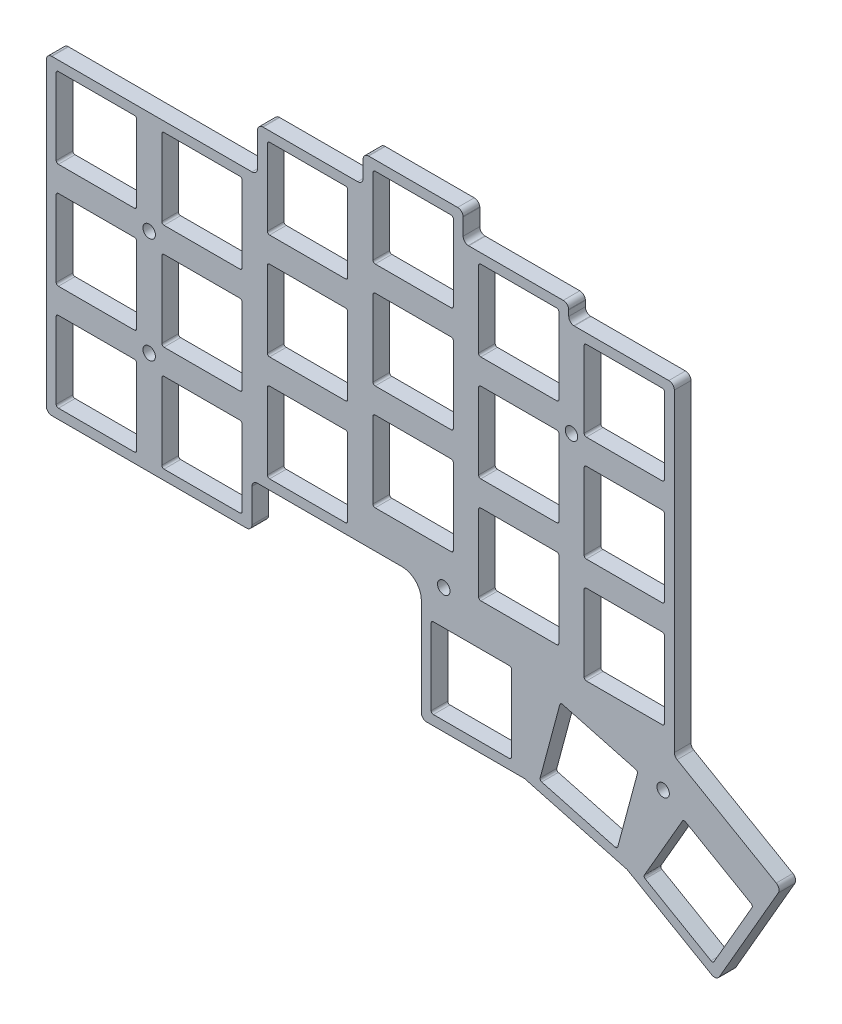
SolidWorks part; units mm, degrees
material "Polyurethane Foam Flexible"
ref_plane "Front Plane" through (0, 0, 0) normal (0, 0, 1) x (1, 0, 0)
ref_plane "Top Plane" through (0, 0, 0) normal (0, 1, 0) x (1, 0, 0)
ref_plane "Right Plane" through (0, 0, 0) normal (1, 0, 0) x (0, 0, -1)
sketch "Sketch1" plane through (0, 0, 0) normal (0, 0, 1) x (1, 0, 0)
  line L84 (-43.4123, 85.1441) -> (-59.4623, 85.1441)
  line L85 (-59.4623, 85.1441) -> (-59.5605, 85.1417)
  line L86 (-60.4623, 84.1441) -> (-60.4623, 81.1441)
  line L87 (-60.4623, 81.1441) -> (-60.4647, 81.0459)
  line L88 (-61.4623, 80.1441) -> (-67.6123, 80.1441)
  line L89 (-67.6123, 80.1441) -> (-72.3623, 80.1441)
  line L90 (-72.3623, 80.1441) -> (-78.5123, 80.1441)
  line L91 (-78.5123, 80.1441) -> (-78.6105, 80.1417)
  line L92 (-79.5123, 79.1441) -> (-79.5123, 73.1441)
  line L93 (-79.5123, 73.1441) -> (-79.5147, 73.0459)
  line L94 (-80.5123, 72.1441) -> (-116.6123, 72.1441)
  line L95 (-116.6123, 72.1441) -> (-116.7105, 72.1417)
  line L96 (-117.6123, 71.1441) -> (-117.6123, 16.9941)
  line L97 (-117.6123, 16.9941) -> (-117.6099, 16.8959)
  line L98 (-116.6123, 15.9941) -> (-101.4373, 15.9941)
  line L99 (-101.4373, 15.9941) -> (-96.6873, 15.9941)
  line L100 (-96.6873, 15.9941) -> (-81.5123, 15.9941)
  line L101 (-81.5123, 15.9941) -> (-81.414, 15.9965)
  line L102 (-80.5123, 16.9941) -> (-80.5123, 22.9941)
  line L103 (-80.5123, 22.9941) -> (-80.5099, 23.0924)
  line L104 (-79.5123, 23.9941) -> (-53.4623, 23.9941)
  line L105 (-53.4623, 23.9941) -> (-53.279, 23.9917)
  line L106 (-49.9623, 20.4941) -> (-49.9623, 2.9441)
  line L107 (-49.9623, 2.9441) -> (-49.9599, 2.8459)
  line L108 (-48.9623, 1.9441) -> (-31.3465, 1.9441)
  line L109 (-31.3465, 1.9441) -> (-12.8184, -3.0205)
  line L110 (-12.8184, -3.0205) -> (2.4374, -11.8284)
  line L111 (2.4374, -11.8284) -> (2.5236, -11.8754)
  line L112 (3.8033, -11.4624) -> (17.3338, 11.973)
  line L113 (17.3338, 11.973) -> (17.3758, 12.0495)
  line L114 (17.4677, 12.4729) -> (17.4677, 76.1441)
  line L115 (17.4677, 76.1441) -> (17.4653, 76.2424)
  line L116 (16.4677, 77.1441) -> (-22.3623, 77.1441)
  line L117 (-22.3623, 77.1441) -> (-22.4605, 77.1465)
  line L118 (-23.3623, 78.1441) -> (-23.3623, 79.1441)
  line L119 (-23.3623, 79.1441) -> (-23.3647, 79.2424)
  line L120 (-24.3623, 80.1441) -> (-30.5123, 80.1441)
  line L121 (-30.5123, 80.1441) -> (-35.2623, 80.1441)
  line L122 (-35.2623, 80.1441) -> (-41.4123, 80.1441)
  line L123 (-41.4123, 80.1441) -> (-41.5105, 80.1465)
  line L124 (-42.4123, 81.1441) -> (-42.4123, 84.1441)
  line L125 (-42.4123, 84.1441) -> (-42.4147, 84.2424)
  line L126 (-43.4123, 85.1441) -> (-59.4623, 85.1441)
  line L127 (-59.4623, 85.1441) -> (-59.5605, 85.1417)
  line L128 (-60.4623, 84.1441) -> (-60.4623, 81.1441)
  line L129 (-60.4623, 81.1441) -> (-60.4647, 81.0459)
  line L130 (-61.4623, 80.1441) -> (-67.6123, 80.1441)
  line L131 (-67.6123, 80.1441) -> (-72.3623, 80.1441)
  line L132 (-72.3623, 80.1441) -> (-78.5123, 80.1441)
  line L133 (-78.5123, 80.1441) -> (-78.6105, 80.1417)
  line L134 (-79.5123, 79.1441) -> (-79.5123, 73.1441)
  line L135 (-79.5123, 73.1441) -> (-79.5147, 73.0459)
  line L136 (-80.5123, 72.1441) -> (-116.6123, 72.1441)
  line L137 (-116.6123, 72.1441) -> (-116.7105, 72.1417)
  line L138 (-117.6123, 71.1441) -> (-117.6123, 16.9941)
  line L139 (-117.6123, 16.9941) -> (-117.6099, 16.8959)
  line L140 (-116.6123, 15.9941) -> (-101.4373, 15.9941)
  line L141 (-101.4373, 15.9941) -> (-96.6873, 15.9941)
  line L142 (-96.6873, 15.9941) -> (-81.5123, 15.9941)
  line L143 (-81.5123, 15.9941) -> (-81.414, 15.9965)
  line L144 (-80.5123, 16.9941) -> (-80.5123, 22.9941)
  line L145 (-80.5123, 22.9941) -> (-80.5099, 23.0924)
  line L146 (-79.5123, 23.9941) -> (-53.4623, 23.9941)
  line L147 (-53.4623, 23.9941) -> (-53.279, 23.9917)
  line L148 (-49.9623, 20.4941) -> (-49.9623, 2.9441)
  line L149 (-49.9623, 2.9441) -> (-49.9599, 2.8459)
  line L150 (-48.9623, 1.9441) -> (-31.3465, 1.9441)
  line L151 (-31.3465, 1.9441) -> (-12.8184, -3.0205)
  line L152 (-12.8184, -3.0205) -> (2.4374, -11.8284)
  line L153 (2.4374, -11.8284) -> (2.5236, -11.8754)
  line L154 (3.8033, -11.4624) -> (17.3338, 11.973)
  line L155 (17.3338, 11.973) -> (17.3758, 12.0495)
  line L156 (17.4677, 12.4729) -> (17.4677, 76.1441)
  line L157 (17.4677, 76.1441) -> (17.4653, 76.2424)
  line L158 (16.4677, 77.1441) -> (-22.3623, 77.1441)
  line L159 (-22.3623, 77.1441) -> (-22.4605, 77.1465)
  line L160 (-23.3623, 78.1441) -> (-23.3623, 79.1441)
  line L161 (-23.3623, 79.1441) -> (-23.3647, 79.2424)
  line L162 (-24.3623, 80.1441) -> (-30.5123, 80.1441)
  line L163 (-30.5123, 80.1441) -> (-35.2623, 80.1441)
  line L164 (-35.2623, 80.1441) -> (-41.4123, 80.1441)
  line L165 (-41.4123, 80.1441) -> (-41.5105, 80.1465)
  line L166 (-42.4123, 81.1441) -> (-42.4123, 84.1441)
  line L167 (-42.4123, 84.1441) -> (-42.4147, 84.2424)
  arc A34 (-42.4147, 84.2424) -> (-43.4123, 85.1441) centre (-43.4078, 84.1464) ccw
  arc A35 (-59.5605, 85.1417) -> (-60.4623, 84.1441) centre (-59.4645, 84.1486) ccw
  arc A36 (-61.4623, 80.1441) -> (-60.4647, 81.0459) centre (-61.4578, 81.1419) ccw
  arc A37 (-78.6105, 80.1417) -> (-79.5123, 79.1441) centre (-78.5145, 79.1486) ccw
  arc A38 (-80.5123, 72.1441) -> (-79.5147, 73.0459) centre (-80.5078, 73.1419) ccw
  arc A39 (-116.7105, 72.1417) -> (-117.6123, 71.1441) centre (-116.6145, 71.1486) ccw
  arc A40 (-117.6099, 16.8959) -> (-116.6123, 15.9941) centre (-116.6167, 16.9919) ccw
  arc A41 (-81.414, 15.9965) -> (-80.5123, 16.9941) centre (-81.51, 16.9897) ccw
  arc A42 (-79.5123, 23.9941) -> (-80.5099, 23.0924) centre (-79.5167, 22.9964) ccw
  arc A43 (-49.9623, 20.4941) -> (-53.279, 23.9917) centre (-53.4603, 20.4984) ccw
  arc A44 (-49.9599, 2.8459) -> (-48.9623, 1.9441) centre (-48.9667, 2.9419) ccw
  arc A45 (2.5236, -11.8754) -> (3.8033, -11.4624) centre (2.9371, -10.9675) ccw
  arc A46 (17.3758, 12.0495) -> (17.4677, 12.4729) centre (16.5045, 12.4604) ccw
  arc A47 (17.4653, 76.2424) -> (16.4677, 77.1441) centre (16.4722, 76.1464) ccw
  arc A48 (-23.3623, 78.1441) -> (-22.4605, 77.1465) centre (-22.3645, 78.1397) ccw
  arc A49 (-23.3647, 79.2424) -> (-24.3623, 80.1441) centre (-24.3578, 79.1464) ccw
  arc A50 (-42.4123, 81.1441) -> (-41.5105, 80.1465) centre (-41.4145, 81.1397) ccw
  arc A51 (-42.4147, 84.2424) -> (-43.4123, 85.1441) centre (-43.4078, 84.1464) ccw
  arc A52 (-59.5605, 85.1417) -> (-60.4623, 84.1441) centre (-59.4645, 84.1486) ccw
  arc A53 (-61.4623, 80.1441) -> (-60.4647, 81.0459) centre (-61.4578, 81.1419) ccw
  arc A54 (-78.6105, 80.1417) -> (-79.5123, 79.1441) centre (-78.5145, 79.1486) ccw
  arc A55 (-80.5123, 72.1441) -> (-79.5147, 73.0459) centre (-80.5078, 73.1419) ccw
  arc A56 (-116.7105, 72.1417) -> (-117.6123, 71.1441) centre (-116.6145, 71.1486) ccw
  arc A57 (-117.6099, 16.8959) -> (-116.6123, 15.9941) centre (-116.6167, 16.9919) ccw
  arc A58 (-81.414, 15.9965) -> (-80.5123, 16.9941) centre (-81.51, 16.9897) ccw
  arc A59 (-79.5123, 23.9941) -> (-80.5099, 23.0924) centre (-79.5167, 22.9964) ccw
  arc A60 (-49.9623, 20.4941) -> (-53.279, 23.9917) centre (-53.4603, 20.4984) ccw
  arc A61 (-49.9599, 2.8459) -> (-48.9623, 1.9441) centre (-48.9667, 2.9419) ccw
  arc A62 (2.5236, -11.8754) -> (3.8033, -11.4624) centre (2.9371, -10.9675) ccw
  arc A63 (17.3758, 12.0495) -> (17.4677, 12.4729) centre (16.5045, 12.4604) ccw
  arc A64 (17.4653, 76.2424) -> (16.4677, 77.1441) centre (16.4722, 76.1464) ccw
  arc A65 (-23.3623, 78.1441) -> (-22.4605, 77.1465) centre (-22.3645, 78.1397) ccw
  arc A66 (-23.3647, 79.2424) -> (-24.3623, 80.1441) centre (-24.3578, 79.1464) ccw
  arc A67 (-42.4123, 81.1441) -> (-41.5105, 80.1465) centre (-41.4145, 81.1397) ccw
  dimension "D1" = 0
extrude "Boss-Extrude1" add sketch "Sketch1" against normal blind 3 from offset 5
sketch "Sketch2" plane through (0, 0, 5) normal (0, 0, 1) x (1, 0, 0)
  line L0 (-118.1123, 53.5941) -> (-99.0623, 53.5941) construction
  line L1 (-118.1123, 72.6441) -> (-99.0623, 72.6441) construction
  line L2 (-118.1123, 72.6441) -> (-118.1123, 53.5941) construction
  line L3 (-118.1123, 53.5941) -> (-99.0623, 53.5941) construction
  line L4 (-99.0623, 72.6441) -> (-99.0623, 53.5941) construction
  line L5 (-118.1123, 72.6441) -> (-99.0623, 53.5941) construction
  line L6 (-118.1123, 53.5941) -> (-99.0623, 72.6441) construction
  line L7 (-118.1123, 53.5941) -> (-118.1123, 34.5441) construction
  line L8 (-118.1123, 34.5441) -> (-99.0623, 34.5441) construction
  line L9 (-99.0623, 53.5941) -> (-99.0623, 34.5441) construction
  line L10 (-118.1123, 53.5941) -> (-99.0623, 34.5441) construction
  line L11 (-118.1123, 34.5441) -> (-99.0623, 53.5941) construction
  line L12 (-118.1123, 34.5441) -> (-99.0623, 34.5441) construction
  line L13 (-118.1123, 34.5441) -> (-118.1123, 15.4941) construction
  line L14 (-118.1123, 15.4941) -> (-99.0623, 15.4941) construction
  line L15 (-99.0623, 34.5441) -> (-99.0623, 15.4941) construction
  line L16 (-118.1123, 34.5441) -> (-99.0623, 15.4941) construction
  line L17 (-118.1123, 15.4941) -> (-99.0623, 34.5441) construction
  line L19 (-101.7373, 55.8691) -> (-115.4373, 55.8691)
  line L20 (-101.3373, 56.2691) -> (-101.3373, 69.9691)
  line L21 (-101.7373, 70.3691) -> (-115.4373, 70.3691)
  line L22 (-115.8373, 56.2691) -> (-115.8373, 69.9691)
  line L23 (-101.3373, 55.8691) -> (-115.8373, 70.3691) construction
  line L24 (-101.3373, 70.3691) -> (-115.8373, 55.8691) construction
  arc A0 (-101.3373, 69.9691) -> (-101.7373, 70.3691) centre (-101.7373, 69.9691) ccw
  arc A1 (-115.4373, 70.3691) -> (-115.8373, 69.9691) centre (-115.4373, 69.9691) ccw
  arc A2 (-101.7373, 55.8691) -> (-101.3373, 56.2691) centre (-101.7373, 56.2691) ccw
  arc A3 (-115.4373, 55.8691) -> (-115.8373, 56.2691) centre (-115.4373, 56.2691) cw
  point P0 (-108.5873, 63.1191)
  point P6 (-108.5873, 44.0691)
  point P12 (-108.5873, 25.0191)
  point P18 (-108.5873, 63.1191)
  dimension "D6" = 0.4
  dimension "D1" = 19.05
  dimension "D2" = 19.05
  dimension "D4" = 14.5
  dimension "D5" = 14.5
  dimension "D3" = 3
extrude "Cut-Extrude1" cut sketch "Sketch2" against normal blind 3
sketch "Sketch3" plane through (0, 0, 2) normal (0, 0, -1) x (-1, 0, 0)
  point P0 (108.5873, 25.0191)
  point P1 (108.5873, 44.0691)
  point P3 (89.5373, 25.0191)
  point P5 (89.5373, 44.0691)
  point P7 (89.5373, 63.1191)
  point P9 (70.4873, 52.0691)
  point P11 (70.4873, 33.0191)
  point P13 (51.4373, 38.0191)
  point P15 (51.4373, 57.0691)
  point P17 (51.4373, 76.1191)
  point P19 (70.4873, 71.1191)
  point P21 (32.3873, 71.1191)
  point P23 (32.3873, 52.0691)
  point P25 (32.3873, 33.0191)
  point P27 (40.9373, 10.9691)
  point P29 (13.3373, 30.0191)
  point P31 (13.3373, 49.0691)
  point P33 (13.3373, 68.1191)
pattern_sketch "Sketch-Pattern1" of "Cut-Extrude1" driven by "Sketch3"
sketch "Sketch4" plane through (0, 0, 5) normal (0, 0, 1) x (1, 0, 0)
  line L0 (-31.3465, 1.9441) -> (-12.8184, -3.0205) construction
  line L7 (-24.4867, 16.9552) -> (-11.2536, 13.4094)
  line L8 (-24.9766, 16.6723) -> (-28.5225, 3.4391)
  line L9 (-28.2396, 2.9493) -> (-15.0064, -0.5966)
  line L10 (-10.9707, 12.9195) -> (-14.5165, -0.3137)
  line L11 (-24.8731, 17.0587) -> (-14.6201, -0.7001) construction
  line L12 (-28.626, 3.0528) -> (-10.8672, 13.3058) construction
  line L13 (2.3073, -9.7037) -> (-9.5573, -2.8537)
  line L14 (2.8537, -9.5573) -> (9.7037, 2.3073)
  line L15 (9.5573, 2.8537) -> (-2.3073, 9.7037)
  line L16 (-9.7037, -2.3073) -> (-2.8537, 9.5573)
  line L17 (2.6537, -9.9037) -> (-2.6537, 9.9037) construction
  line L18 (9.9037, 2.6537) -> (-9.9037, -2.6537) construction
  line L21 (-12.8184, -3.0205) -> (2.4374, -11.8284) construction
  arc A0 (9.7037, 2.3073) -> (9.5573, 2.8537) centre (9.3573, 2.5073) ccw
  arc A1 (-2.3073, 9.7037) -> (-2.8537, 9.5573) centre (-2.5073, 9.3573) ccw
  arc A2 (2.3073, -9.7037) -> (2.8537, -9.5573) centre (2.5073, -9.3573) ccw
  arc A3 (-9.5573, -2.8537) -> (-9.7037, -2.3073) centre (-9.3573, -2.5073) cw
  arc A4 (-24.4867, 16.9552) -> (-24.9766, 16.6723) centre (-24.5903, 16.5688) ccw
  arc A5 (-11.2536, 13.4094) -> (-10.9707, 12.9195) centre (-11.3571, 13.023) cw
  arc A6 (-15.0064, -0.5966) -> (-14.5165, -0.3137) centre (-14.9029, -0.2102) ccw
  arc A7 (-28.5225, 3.4391) -> (-28.2396, 2.9493) centre (-28.1361, 3.3356) ccw
  point P6 (-19.7466, 8.1793)
  point P12 (0, 0)
  dimension "D5" = 0.4
  dimension "D3" = 14.5
  dimension "D4" = 14.5
extrude "Cut-Extrude2" cut sketch "Sketch4" against normal blind 3
sketch "Sketch5" plane through (0, 0, 5) normal (0, 0, 1) x (1, 0, 0)
  line L0 (-12.9037, 77.1441) -> (-5.3123, 77.1441)
  line L1 (16.4677, 77.1441) -> (-22.3623, 77.1441) construction
  line L2 (-4.3123, 76.1441) -> (-4.3123, 19.5215)
  line L3 (-3.8123, 18.6555) -> (14.0749, 8.3284)
  line L4 (3.8033, -11.4624) -> (17.3338, 11.973) construction
  line L6 (24.7528, -3.8699) -> (24.7528, 82.8825)
  line L7 (24.7528, 82.8825) -> (-12.9037, 94.3839)
  line L8 (-12.9037, 94.3839) -> (-12.9037, 77.1441)
  line L9 (-12.9037, 77.1441) -> (-12.9037, 75.3691) construction
  line L10 (-6.4873, 75.3691) -> (-20.1873, 75.3691) construction
  line L11 (-6.0873, 68.1191) -> (-4.3123, 68.1191) construction
  line L12 (-6.0873, 61.2691) -> (-6.0873, 74.9691) construction
  line L13 (3.625, 6.2787) -> (7.125, 12.3409) construction
  line L14 (9.5573, 2.8537) -> (-2.3073, 9.7037) construction
  line L15 (14.4409, 6.9623) -> (7.7543, -4.6191)
  line L16 (7.7543, -4.6191) -> (24.7528, -3.8699)
  arc A0 (-5.3123, 77.1441) -> (-4.3123, 76.1441) centre (-5.3123, 76.1441) cw
  arc A1 (-4.3123, 19.5215) -> (-3.8123, 18.6555) centre (-3.3123, 19.5215) ccw
  arc A2 (14.0749, 8.3284) -> (14.4409, 6.9623) centre (13.5749, 7.4623) cw
  point P25 (-4.3123, 77.1441)
  point P30 (14.9409, 7.8284)
  dimension "D1" = 1
  dimension "D2" = 7
extrude "Cut-Extrude3" cut sketch "Sketch5" against normal blind 3
sketch "Sketch6" plane through (0, 0, 2) normal (0, 0, -1) x (-1, 0, 0)
  circle A0 centre (99.0623, 34.5441) radius 1.125
  circle A1 centre (99.0623, 53.5941) radius 1.125
  circle A2 centre (45.9123, 24.4941) radius 1.125
  circle A3 centre (6.3338, 12.6346) radius 1.125
  circle A4 centre (22.8623, 60.0941) radius 1.125
  dimension "D1" = 2.25
extrude "Cut-Extrude4" cut sketch "Sketch6" against normal blind 3
